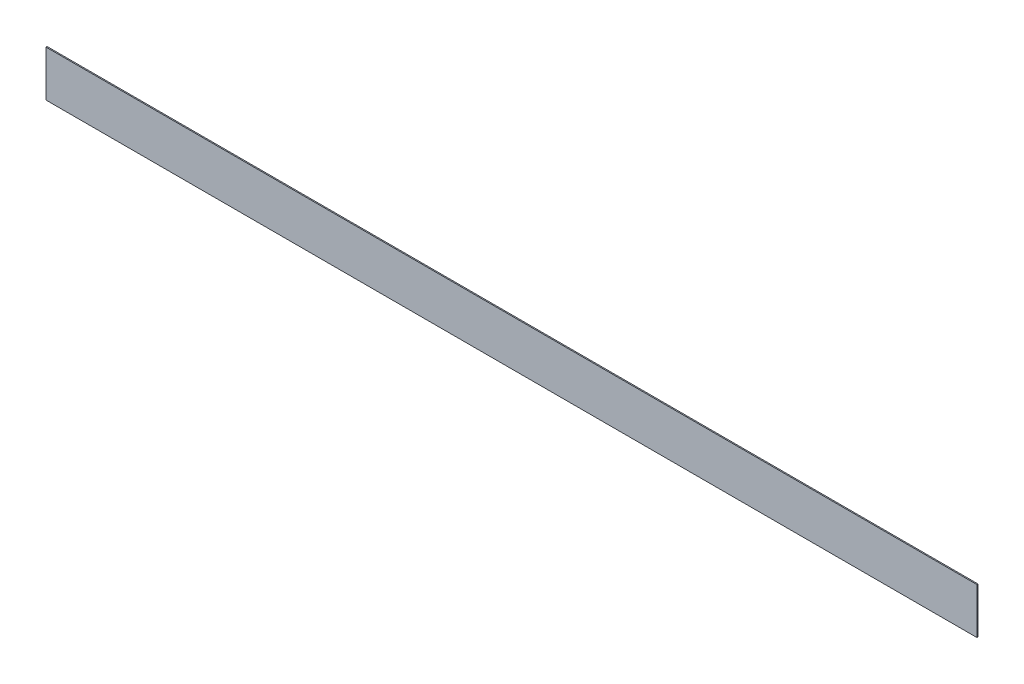
SolidWorks part; units mm, degrees
ref_plane "Front Plane" through (0, 0, 0) normal (0, 0, 1) x (1, 0, 0)
ref_plane "Top Plane" through (0, 0, 0) normal (0, 1, 0) x (1, 0, 0)
ref_plane "Right Plane" through (0, 0, 0) normal (1, 0, 0) x (0, 0, -1)
other "Configuration Table"
sketch "Sketch1" plane through (0, 0, 0) normal (0, 0, 1) x (1, 0, 0)
  line L1 (66, 120) -> (1334, 120)
  line L2 (66, 120) -> (66, 182.5)
  line L3 (66, 182.5) -> (1334, 182.5)
  line L4 (1334, 120) -> (1334, 182.5)
extrude "STORE_panel_bant_alt_1" add sketch "Sketch1" along normal blind 1.5 from offset 38.5 separate body
